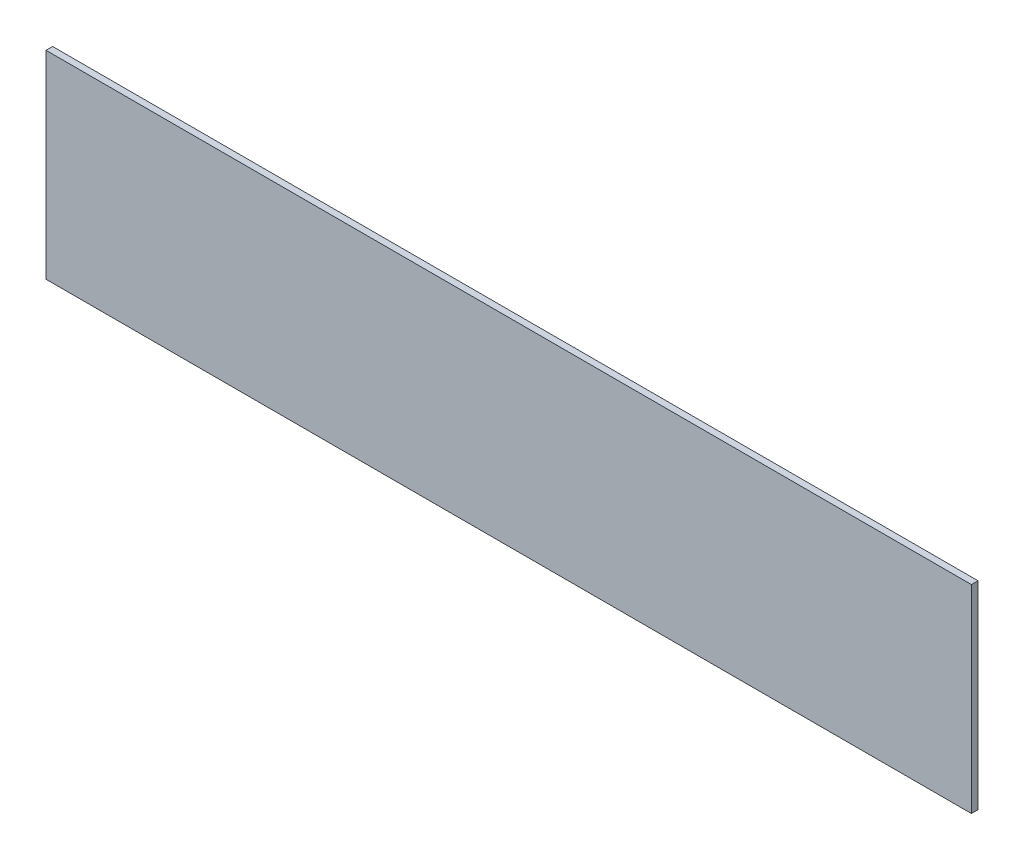
SolidWorks part; units mm, degrees
ref_plane "Front Plane" through (0, 0, 0) normal (0, 0, 1) x (1, 0, 0)
ref_plane "Top Plane" through (0, 0, 0) normal (0, 1, 0) x (1, 0, 0)
ref_plane "Right Plane" through (0, 0, 0) normal (1, 0, 0) x (0, 0, -1)
sketch "Sketch1" plane through (0, 0, 0) normal (0, 0, 1) x (1, 0, 0)
  line L5 (-167.7032, 80.3887) -> (112.2968, 80.3887)
  line L6 (-167.7032, 80.3887) -> (-167.7032, 20.3887)
  line L7 (-167.7032, 20.3887) -> (112.2968, 20.3887)
  line L8 (112.2968, 80.3887) -> (112.2968, 20.3887)
  dimension "D1" = 280
  dimension "D2" = 60
extrude "Boss-Extrude1" add sketch "Sketch1" along normal blind 2
